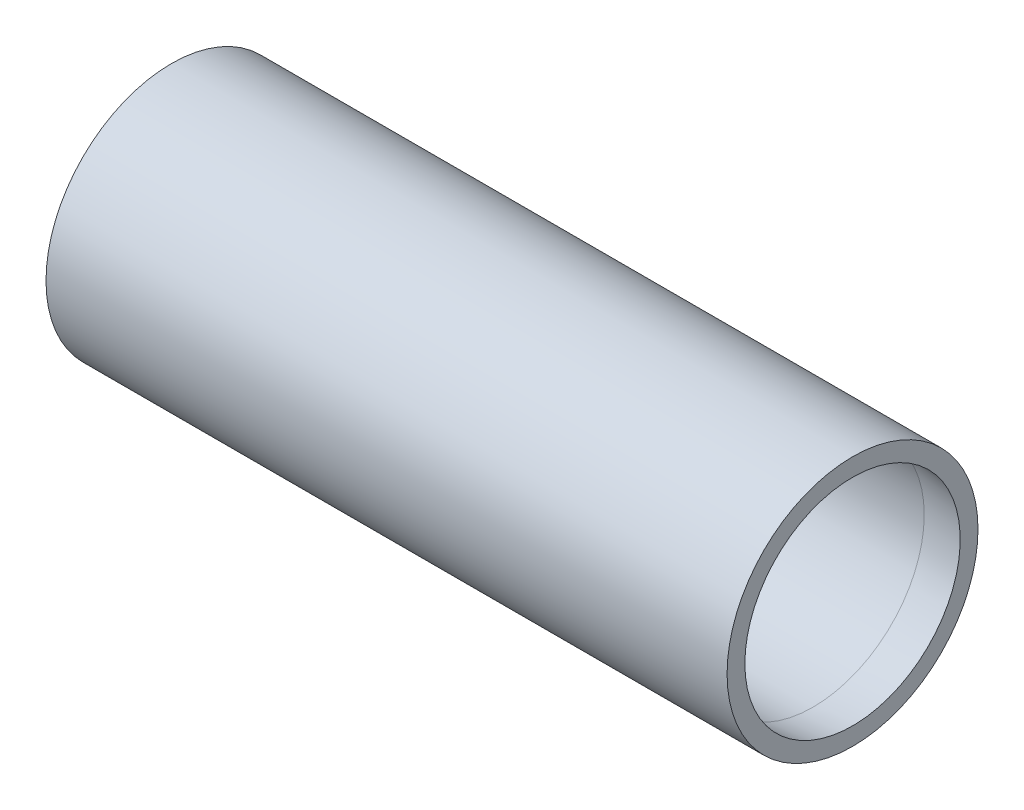
SolidWorks part; units mm, degrees
ref_plane "Front Plane" through (0, 0, 0) normal (0, 0, 1) x (1, 0, 0)
ref_plane "Top Plane" through (0, 0, 0) normal (0, 1, 0) x (1, 0, 0)
ref_plane "Right Plane" through (0, 0, 0) normal (1, 0, 0) x (0, 0, -1)
sketch "Sketch1" plane through (0, 0, 0) normal (0, 0, 1) x (1, 0, 0)
  line L0 (0, 17.5) -> (95, 17.5)
  line L1 (0, 17.5) -> (0, 15.5)
  line L2 (0, 15.5) -> (89.5, 15.5)
  line L3 (95, 15.0188) -> (95, 17.5)
  line L4 (0, 0) -> (189.0464, 0) construction
  line L5 (89.5, 15.5) -> (95, 15.0188)
  dimension "D1" = 95
  dimension "D2" = 31
  dimension "D3" = 35
  dimension "D4" = 5.5
  dimension "D5" = 5
revolve "Revolve1" add sketch "Sketch1" angle 360 about L4
cosmetic thread "Cosmetic Thread1" parameters "D1"=6, "D2"=32
